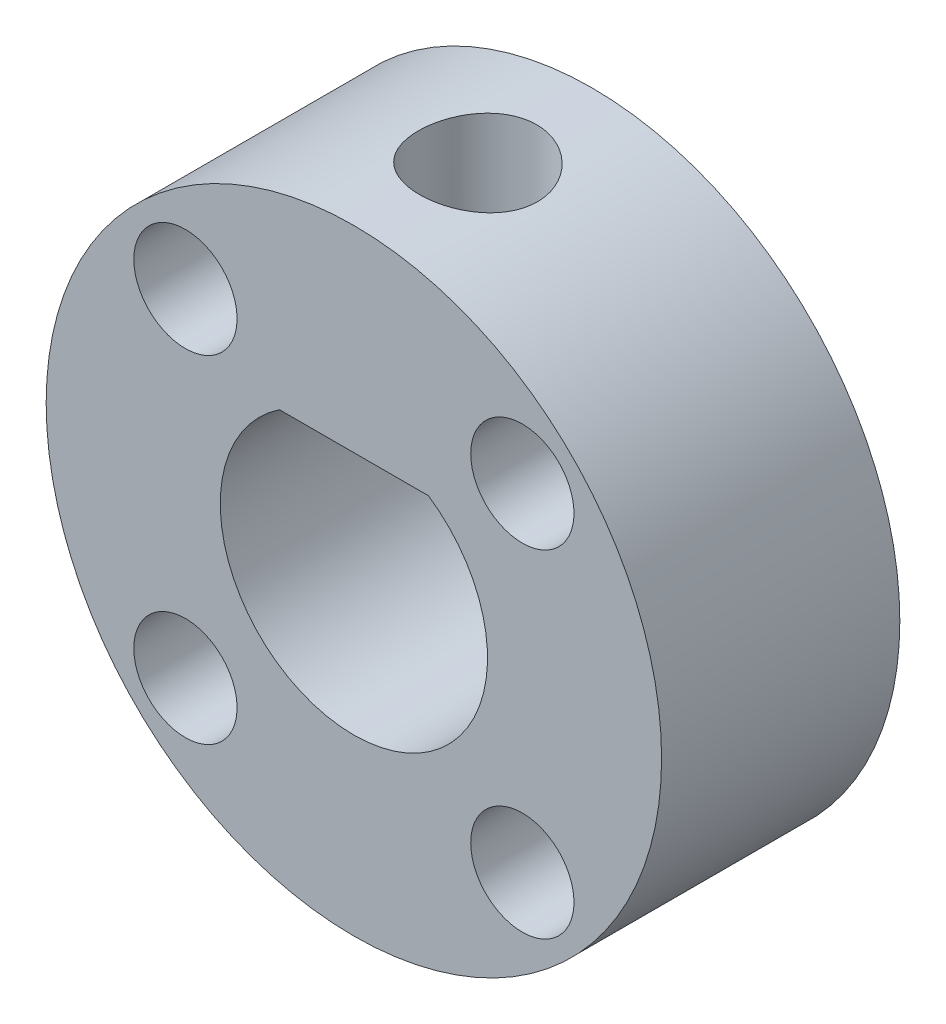
SolidWorks part; units mm, degrees
ref_plane "Front" through (0, 0, 0) normal (0, 0, 1) x (1, 0, 0)
ref_plane "Top" through (0, 0, 0) normal (0, 1, 0) x (1, 0, 0)
ref_plane "Right" through (0, 0, 0) normal (1, 0, 0) x (0, 0, -1)
sketch "Sketch1" plane through (0, 0, 0) normal (0, 1, 0) x (1, 0, 0)
  line L0 (7.75, 0) -> (0, 0)
  line L1 (0, 0) -> (0, -6)
  line L2 (0, -6) -> (7.75, -6)
  line L3 (7.75, -6) -> (7.75, 0)
  line L4 (0, 0) -> (0, -6) construction
revolve "Revolve1" add sketch "Sketch1" angle 360 about L4
sketch "Sketch2" plane through (0, 0, 0) normal (0, 0, -1) x (-1, 0, 0)
  line L0 (1.8762, 2.794) -> (-1.8762, 2.794)
  arc A0 (-1.8762, 2.794) -> (1.8762, 2.794) centre (0, 0) ccw
extrude "Cut-Extrude1" cut sketch "Sketch2" against normal through all
hole_wizard "Ø3.0 (3) Diameter Hole1" positions "Sketch4" profile "Sketch3" hole size "Ø3.0" standard "ANSI Metric"
sketch "Sketch4" plane through (0, 2.794, 0) normal (0, -1, 0) x (-1, 0, 0)
  point P0 (-0.1238, -3)
sketch "Sketch3" plane through (0.1238, 2.794, 3) normal (1, 0, 0) x (0, 0, -1)
  line L0 (0, 0) -> (0, 4.956)
  line L1 (0, 4.956) -> (1.5, 4.956)
  line L2 (1.5, 4.956) -> (1.5, 0)
  line L5 (1.5, 0) -> (0, 0)
  line L11 (0, -6.35) -> (0, 107.95) construction
  dimension "Thru Hole Dia." = 3
  dimension "Thru Hole Depth" = 4.956
hole_wizard "Ø2.6 (2.6) Diameter Hole1" positions "Sketch6" profile "Sketch5" hole size "Ø2.6" standard "ANSI Metric"
sketch "Sketch6" plane through (0, 0, 0) normal (0, 0, -1) x (-1, 0, 0)
  point P0 (-4.2426, -4.2426)
  point P1 (4.2426, 4.2426)
  point P2 (-4.2426, 4.2426)
  point P3 (4.2426, -4.2426)
sketch "Sketch5" plane through (4.2426, -4.2426, 0) normal (1, 0, 0) x (0, 1, 0)
  line L0 (0, 0) -> (0, 6)
  line L1 (0, 6) -> (1.3, 6)
  line L2 (1.3, 6) -> (1.3, 0)
  line L5 (1.3, 0) -> (0, 0)
  line L11 (0, -6.35) -> (0, 107.95) construction
  dimension "Thru Hole Dia." = 2.6
  dimension "Thru Hole Depth" = 6
